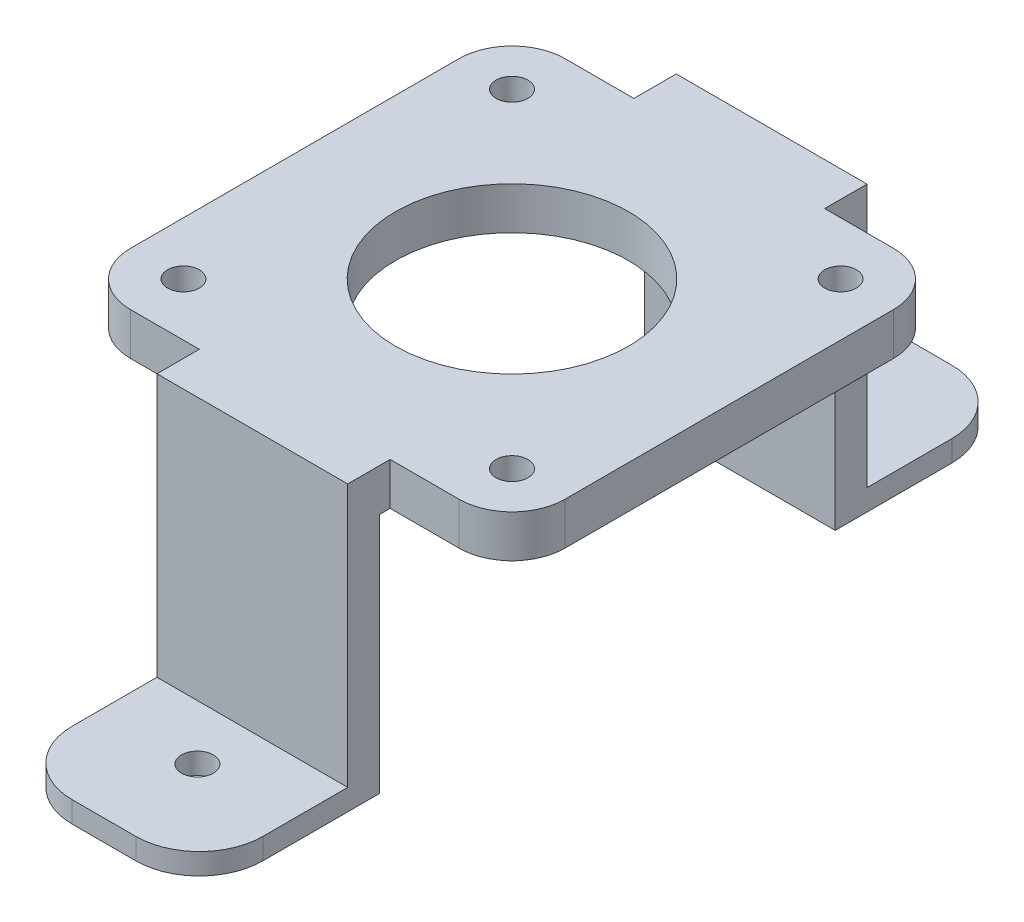
SolidWorks part; units mm, degrees
ref_plane "Спереди" through (0, 0, 0) normal (0, 0, 1) x (1, 0, 0)
ref_plane "Сверху" through (0, 0, 0) normal (0, 1, 0) x (1, 0, 0)
ref_plane "Справа" through (0, 0, 0) normal (1, 0, 0) x (0, 0, -1)
other "Configuration Table"
sketch "Эскиз2" plane through (0, 0, 0) normal (0, 1, 0) x (1, 0, 0)
  line L0 (0, 0) -> (-63.8997, 0) construction
  line L1 (-15.5, -20.5) -> (15.5, -20.5)
  line L2 (-20.5, -15.5) -> (-20.5, 15.5)
  line L3 (-15.5, 20.5) -> (15.5, 20.5)
  line L4 (20.5, -15.5) -> (20.5, 15.5)
  line L5 (-20.5, -20.5) -> (20.5, 20.5) construction
  line L6 (-20.5, 20.5) -> (20.5, -20.5) construction
  circle A0 centre (0, 0) radius 11
  circle A1 centre (-15.5, 15.5) radius 1.5
  circle A2 centre (15.5, -15.5) radius 1.5
  circle A3 centre (-15.5, -15.5) radius 1.5
  circle A4 centre (15.5, 15.5) radius 1.5
  arc A5 (-15.5, 20.5) -> (-20.5, 15.5) centre (-15.5, 15.5) ccw
  arc A6 (20.5, 15.5) -> (15.5, 20.5) centre (15.5, 15.5) ccw
  arc A7 (-15.5, -20.5) -> (-20.5, -15.5) centre (-15.5, -15.5) cw
  arc A8 (15.5, -20.5) -> (20.5, -15.5) centre (15.5, -15.5) ccw
  point P0 (0, 0)
  dimension "D3" = 22
  dimension "D4" = 3
  dimension "D7" = 5
  dimension "D8" = 5
  dimension "D9" = 5
  dimension "D10" = 5
  dimension "D1" = 41
  dimension "D2" = 41
  dimension "D5" = 31
  dimension "D6" = 31
extrude "дырка" add sketch "Эскиз2" along normal blind 4
sketch "Эскиз3" plane through (0, 0, 20.5) normal (0, 0, 1) x (1, 0, 0)
  line L0 (-15.5, 4) -> (15.5, 4) construction
  line L1 (-9, 4) -> (9, 4)
  line L2 (-9, 4) -> (-9, -22.8)
  line L3 (-9, -22.8) -> (9, -22.8)
  line L4 (9, 4) -> (9, -22.8)
  line L5 (-20.5, 4) -> (-20.5, 0) construction
  dimension "D1" = 18
  dimension "D2" = 11.5
  dimension "D3" = 26.8
  dimension "D4" = 26.8
extrude "нога" add sketch "Эскиз3" along normal blind 4 contours L1 L4 L3 L2
sketch "Эскиз4" plane through (0, -22.8, 0) normal (0, -1, 0) x (1, 0, 0)
  line L1 (9, 24.5) -> (-9, 24.5)
  line L2 (9, 24.5) -> (9, 32.5)
  line L3 (3, 38.5) -> (-3, 38.5)
  line L4 (-9, 24.5) -> (-9, 32.5)
  arc A0 (-3, 38.5) -> (-9, 32.5) centre (-3, 32.5) ccw
  arc A1 (3, 38.5) -> (9, 32.5) centre (3, 32.5) cw
  point P7 (-9, 38.5)
  dimension "D2" = 6
  dimension "D3" = 6
  dimension "D1" = 14
extrude "нога с дыркой" add sketch "Эскиз4" against normal blind 2
sketch "Эскиз5" plane through (0, -20.8, 0) normal (0, 1, 0) x (1, 0, 0)
  circle A0 centre (0, -29.6787) radius 1.5
  dimension "D1" = 3
extrude "дырка на ноге" cut sketch "Эскиз5" against normal through all contours A0
sketch "Эскиз7" plane through (0, 0, 20.5) normal (0, 0, -1) x (-1, 0, 0)
  line L0 (15.5, 0) -> (-15.5, 0) construction
  line L1 (9, -22.8) -> (-9, -22.8)
  line L2 (9, -22.8) -> (9, 0)
  line L3 (9, 0) -> (-9, 0)
  line L4 (-9, -22.8) -> (-9, 0)
  line L5 (-9, 0) -> (-9, -22.8) construction
extrude "Вырез-Вытянуть1" cut sketch "Эскиз7" against normal blind 1
mirror "Зеркальное отражение1" about plane through (0, 0, 0) normal (0, 0, 1) of "Вырез-Вытянуть1", "нога", "нога с дыркой", "дырка на ноге"
